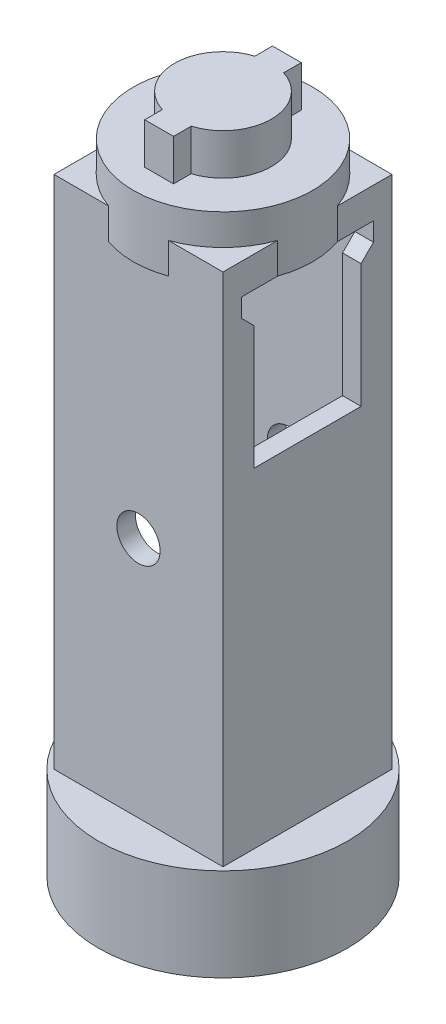
SolidWorks part; units mm, degrees
ref_plane "Front Plane" through (0, 0, 0) normal (0, 0, 1) x (1, 0, 0)
ref_plane "Top Plane" through (0, 0, 0) normal (0, 1, 0) x (1, 0, 0)
ref_plane "Right Plane" through (0, 0, 0) normal (1, 0, 0) x (0, 0, -1)
sketch "Sketch2" plane through (0, 0, 0) normal (0, 1, 0) x (1, 0, 0)
  line L1 (-8.9179, -4.2451) -> (-4.2579, -4.2451)
  line L2 (-8.9179, -4.2451) -> (-8.9179, 16.4149)
  line L3 (-8.9179, 16.4149) -> (-4.2579, 16.4149)
  line L4 (-4.2579, -4.2451) -> (-4.2579, 16.4149)
  line L5 (-8.9179, -4.2451) -> (-4.2579, 16.4149) construction
  line L6 (-8.9179, 16.4149) -> (-4.2579, -4.2451) construction
  circle A0 centre (-6.5879, 6.0849) radius 7.83
  dimension "D1" = 15.66
  dimension "D2" = 4.66
  dimension "D3" = 20.66
extrude "Boss-Extrude1" add sketch "Sketch2" along normal blind 6.66 contours L4 A0 | L4 A0 L2 | A0 L2 L1 L4 | L2 A0 | A0 L4 L3 L2
sketch "Sketch3" plane through (0, 0, 0) normal (0, -1, 0) x (1, 0, 0)
  line L0 (-6.5879, 4.2451) -> (-6.5879, -16.4149)
  line L1 (-8.9179, 4.2451) -> (-4.2579, 4.2451) construction
  line L2 (-8.9179, -16.4149) -> (-4.2579, -16.4149) construction
  circle A0 centre (-6.5879, -6.0849) radius 14.5
  arc M1 (-4.2579, -13.5602) -> (-4.2579, 1.3904) centre (-6.5879, -6.0849) ccw
  line M2 (-4.2579, 1.3904) -> (-4.2579, 4.2451)
  line M3 (-4.2579, 4.2451) -> (-8.9179, 4.2451)
  line M4 (-8.9179, 4.2451) -> (-8.9179, 1.3904)
  arc M5 (-8.9179, 1.3904) -> (-8.9179, -13.5602) centre (-6.5879, -6.0849) ccw
  line M6 (-8.9179, -13.5602) -> (-8.9179, -16.4149)
  line M7 (-8.9179, -16.4149) -> (-4.2579, -16.4149)
  line M8 (-4.2579, -16.4149) -> (-4.2579, -13.5602)
  dimension "D1" = 29
extrude "Boss-Extrude2" add sketch "Sketch3" along normal blind 10 contours A0 M1 M8 M7 M6 M5 M4 M3 M2 | L0 M3 M7 M8 M1 M2 | L0 M3 M4 M5 M6 M7
sketch "Sketch5" plane through (0, -10, 0) normal (0, -1, 0) x (1, 0, 0)
  line L1 (-17.2579, -16.7549) -> (4.0821, -16.7549)
  line L2 (-17.2579, -16.7549) -> (-17.2579, 4.5851)
  line L3 (-17.2579, 4.5851) -> (4.0821, 4.5851)
  line L4 (4.0821, -16.7549) -> (4.0821, 4.5851)
  line L5 (-17.2579, -16.7549) -> (4.0821, 4.5851) construction
  line L6 (-17.2579, 4.5851) -> (4.0821, -16.7549) construction
  line L7 (-20.2579, -19.7549) -> (7.0821, -19.7549)
  line L8 (-20.2579, -19.7549) -> (-20.2579, 7.5851)
  line L9 (-20.2579, 7.5851) -> (7.0821, 7.5851)
  line L10 (7.0821, -19.7549) -> (7.0821, 7.5851)
  line L11 (-20.2579, -19.7549) -> (7.0821, 7.5851) construction
  line L12 (-20.2579, 7.5851) -> (7.0821, -19.7549) construction
  point P0 (-6.5879, -6.0849)
  point P6 (-6.5879, -6.0849)
  dimension "D1" = 21.34
  dimension "D2" = 27.34
extrude "Boss-Extrude3" add sketch "Sketch5" along normal blind 83.34 from offset 5 offset against normal yes
sketch "Sketch6" plane through (0, -10, 0) normal (0, -1, 0) x (1, 0, 0)
  line L1 (-17.2579, 4.5851) -> (4.0821, 4.5851)
  line L2 (-17.2579, 4.5851) -> (-17.2579, -16.7549)
  line L3 (-17.2579, -16.7549) -> (4.0821, -16.7549)
  line L4 (4.0821, 4.5851) -> (4.0821, -16.7549)
extrude "Boss-Extrude4" add sketch "Sketch6" against normal blind 5
sketch "Sketch8" plane through (-20.2579, 0, 0) normal (-1, 0, 0) x (0, 0, 1)
  line L1 (-16.7549, -88.34) -> (4.5851, -88.34)
  line L2 (-16.7549, -88.34) -> (-16.7549, -10)
  line L3 (-16.7549, -10) -> (4.5851, -10)
  line L4 (4.5851, -88.34) -> (4.5851, -10)
  dimension "D1" = 21.34
  dimension "D2" = 78.34
extrude "Cut-Extrude1" cut sketch "Sketch8" against normal blind 5
sketch "Sketch9" plane through (4.0821, 0, 0) normal (-1, 0, 0) x (0, 0, 1)
  line L0 (-16.7549, -88.34) -> (-16.7549, -10) construction
  line L1 (4.5851, -10) -> (-16.7549, -10)
  line L2 (4.5851, -10) -> (4.5851, -13)
  line L3 (4.5851, -13) -> (-16.7549, -13)
  line L4 (-16.7549, -10) -> (-16.7549, -13)
  dimension "D1" = 3
extrude "Cut-Extrude2" cut sketch "Sketch9" against normal blind 5
sketch "Sketch10" plane through (0, -88.34, 0) normal (0, -1, 0) x (1, 0, 0)
  line L2 (7.0821, 7.5851) -> (-20.2579, 7.5851)
  line L3 (7.0821, 7.5851) -> (7.0821, -19.7549)
  line L4 (7.0821, -19.7549) -> (-20.2579, -19.7549)
  line L5 (-20.2579, 7.5851) -> (-20.2579, -19.7549)
extrude "Boss-Extrude5" add sketch "Sketch10" along normal blind 3
sketch "Sketch11" plane through (0, -91.34, 0) normal (0, -1, 0) x (-1, 0, 0)
  circle A0 centre (6.5879, 6.0849) radius 20.15
  dimension "D1" = 40.3
extrude "Boss-Extrude6" add sketch "Sketch11" along normal blind 12
sketch "Sketch12" plane through (0, -103.34, 0) normal (0, -1, 0) x (1, 0, 0)
  circle A0 centre (-6.5879, -6.0849) radius 16.15
  dimension "32" = 32.3
extrude "Cut-Extrude3" cut sketch "Sketch12" against normal blind 10.5
sketch "Sketch13" plane through (0, -92.84, 0) normal (0, -1, 0) x (1, 0, 0)
  circle A0 centre (-6.5879, -6.0849) radius 12.15
  dimension "D1" = 24.3
extrude "Cut-Extrude4" cut sketch "Sketch13" against normal blind 0.5
sketch "Sketch14" plane through (0, -91.34, 0) normal (0, 1, 0) x (1, 0, 0)
  line L0 (-6.5879, -14.0651) -> (-6.5879, 26.2349)
  circle A0 centre (-6.5879, 6.0849) radius 20.15 construction
  circle A1 centre (-6.5879, 6.0849) radius 20.15
  circle M1 centre (-6.5879, 6.0849) radius 20.15
  line M2 (-20.2579, 19.7549) -> (7.0821, 19.7549)
  line M3 (7.0821, 19.7549) -> (7.0821, -7.5851)
  line M4 (7.0821, -7.5851) -> (-20.2579, -7.5851)
  line M5 (-20.2579, -7.5851) -> (-20.2579, 19.7549)
extrude "Boss-Extrude7" add sketch "Sketch14" along normal up to surface (3 mm away) contours L0 M1 M2 M3 M4 | L0 M1 M4 M5 M2 up to face at (-8.0879, -88.34, -6.0849)
sketch "Sketch19" plane through (0, 0, 7.5851) normal (0, 0, 1) x (1, 0, 0)
  line L0 (-6.5879, -10) -> (-6.5879, -88.34)
  line L1 (-11.4233, -10) -> (-1.7525, -10) construction
  line L2 (7.0821, -88.34) -> (-20.2579, -88.34) construction
  circle A0 centre (-6.5879, -49.17) radius 3.5
  dimension "D1" = 7
extrude "Cut-Extrude5" cut sketch "Sketch19" against normal through all contours A0
sketch "Sketch20" plane through (4.0821, 0, 0) normal (-1, 0, 0) x (0, 0, 1)
  line L5 (-16.7549, -10) -> (-16.7549, -15)
  line L6 (-16.7549, -35) -> (-14.7549, -35)
  line L7 (-16.7549, -15) -> (4.5851, -15)
  line L8 (-16.7549, -15) -> (-16.7549, -35)
  line L9 (-16.7549, -35) -> (4.5851, -35)
  line L10 (4.5851, -15) -> (4.5851, -35)
  line L11 (4.5851, -15) -> (2.5851, -15)
  line L13 (-14.7549, -35) -> (2.5851, -35)
  line L14 (-14.7549, -35) -> (-14.7549, -15)
  line L15 (-14.7549, -15) -> (2.5851, -15)
  line L16 (2.5851, -35) -> (2.5851, -15)
  dimension "D1" = 5
  dimension "D2" = 20
  dimension "D3" = 2
  dimension "D4" = 2
extrude "Cut-Extrude6" cut sketch "Sketch20" against normal through all contours L9 L16 L7 L14
sketch "Sketch21" plane through (4.0821, 0, 0) normal (-1, 0, 0) x (0, 0, 1)
  line L0 (-14.7549, -15) -> (-16.7549, -13)
  line L1 (-16.7549, -13) -> (4.5851, -13)
  line L2 (4.5851, -13) -> (2.5851, -15)
  line L3 (2.5851, -15) -> (-14.7549, -15)
extrude "Cut-Extrude7" cut sketch "Sketch21" against normal through all
